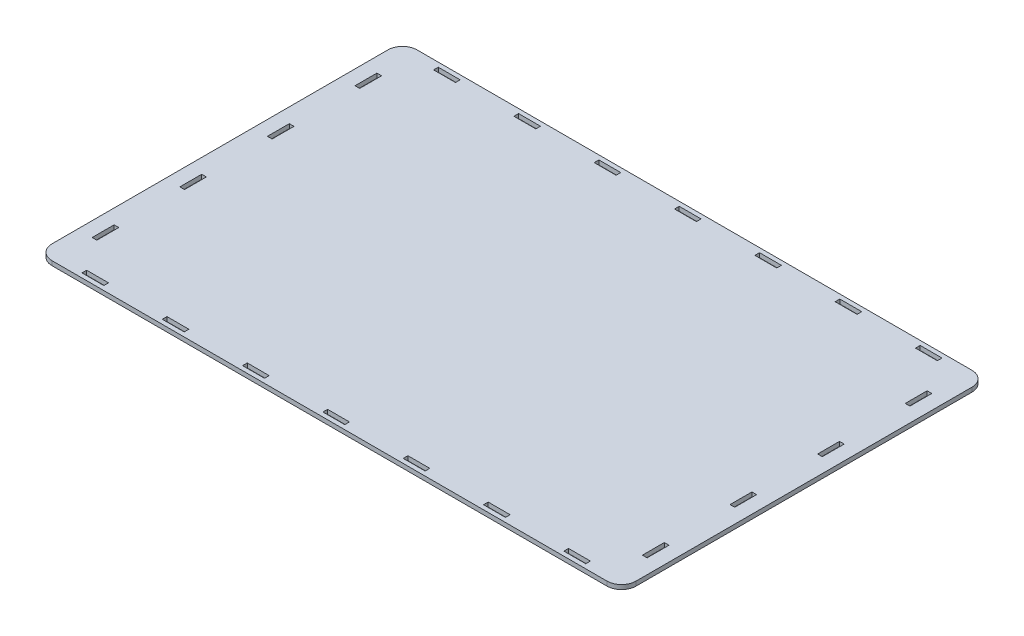
SolidWorks part; units mm, degrees
ref_plane "Front Plane" through (0, 0, 0) normal (0, 0, 1) x (1, 0, 0)
ref_plane "Top Plane" through (0, 0, 0) normal (0, 1, 0) x (1, 0, 0)
ref_plane "Right Plane" through (0, 0, 0) normal (1, 0, 0) x (0, 0, -1)
sketch "Sketch1" plane through (0, 0, 0) normal (0, 1, 0) x (1, 0, 0)
  line L0 (82.5, 3) -> (82.5, 6.2)
  line L1 (0, 0) -> (400, 0)
  line L2 (0, 0) -> (0, 250)
  line L3 (0, 250) -> (400, 250)
  line L5 (27.5, 3) -> (42.5, 3)
  line L6 (27.5, 3) -> (27.5, 6.2)
  line L7 (27.5, 6.2) -> (42.5, 6.2)
  line L8 (42.5, 3) -> (42.5, 6.2)
  line L9 (82.5, 3) -> (97.5, 3)
  line L10 (97.5, 3) -> (97.5, 6.2)
  line L11 (82.5, 6.2) -> (97.5, 6.2)
  line L12 (137.5, 3) -> (137.5, 6.2)
  line L13 (137.5, 3) -> (152.5, 3)
  line L14 (152.5, 3) -> (152.5, 6.2)
  line L15 (137.5, 6.2) -> (152.5, 6.2)
  line L16 (192.5, 3) -> (192.5, 6.2)
  line L17 (192.5, 3) -> (207.5, 3)
  line L18 (207.5, 3) -> (207.5, 6.2)
  line L19 (192.5, 6.2) -> (207.5, 6.2)
  line L20 (247.5, 3) -> (247.5, 6.2)
  line L21 (247.5, 3) -> (262.5, 3)
  line L22 (262.5, 3) -> (262.5, 6.2)
  line L23 (247.5, 6.2) -> (262.5, 6.2)
  line L24 (302.5, 3) -> (302.5, 6.2)
  line L25 (302.5, 3) -> (317.5, 3)
  line L26 (317.5, 3) -> (317.5, 6.2)
  line L27 (302.5, 6.2) -> (317.5, 6.2)
  line L28 (357.5, 3) -> (357.5, 6.2)
  line L29 (357.5, 3) -> (372.5, 3)
  line L30 (372.5, 3) -> (372.5, 6.2)
  line L31 (357.5, 6.2) -> (372.5, 6.2)
  line L32 (0, 125) -> (400, 125) construction
  line L33 (357.5, 247) -> (372.5, 247)
  line L34 (372.5, 247) -> (372.5, 243.8)
  line L35 (357.5, 243.8) -> (372.5, 243.8)
  line L36 (357.5, 247) -> (357.5, 243.8)
  line L37 (302.5, 247) -> (317.5, 247)
  line L38 (317.5, 247) -> (317.5, 243.8)
  line L39 (302.5, 243.8) -> (317.5, 243.8)
  line L40 (302.5, 247) -> (302.5, 243.8)
  line L41 (247.5, 247) -> (262.5, 247)
  line L42 (262.5, 247) -> (262.5, 243.8)
  line L43 (247.5, 243.8) -> (262.5, 243.8)
  line L44 (247.5, 247) -> (247.5, 243.8)
  line L45 (192.5, 247) -> (207.5, 247)
  line L46 (207.5, 247) -> (207.5, 243.8)
  line L47 (192.5, 243.8) -> (207.5, 243.8)
  line L48 (192.5, 247) -> (192.5, 243.8)
  line L49 (27.5, 243.8) -> (42.5, 243.8)
  line L50 (42.5, 247) -> (42.5, 243.8)
  line L51 (27.5, 247) -> (42.5, 247)
  line L52 (27.5, 247) -> (27.5, 243.8)
  line L53 (82.5, 247) -> (97.5, 247)
  line L54 (97.5, 247) -> (97.5, 243.8)
  line L55 (82.5, 243.8) -> (97.5, 243.8)
  line L56 (82.5, 247) -> (82.5, 243.8)
  line L57 (137.5, 247) -> (152.5, 247)
  line L58 (152.5, 247) -> (152.5, 243.8)
  line L59 (137.5, 243.8) -> (152.5, 243.8)
  line L60 (137.5, 247) -> (137.5, 243.8)
  line L61 (200, 0) -> (200, 250) construction
  line L62 (10, 102.5) -> (10, 87.5)
  line L63 (10, 42.5) -> (13.2, 42.5)
  line L64 (10, 42.5) -> (10, 27.5)
  line L65 (10, 27.5) -> (13.2, 27.5)
  line L66 (13.2, 42.5) -> (13.2, 27.5)
  line L67 (10, 102.5) -> (13.2, 102.5)
  line L68 (13.2, 102.5) -> (13.2, 87.5)
  line L69 (10, 87.5) -> (13.2, 87.5)
  line L70 (10, 162.5) -> (10, 147.5)
  line L71 (10, 162.5) -> (13.2, 162.5)
  line L72 (13.2, 162.5) -> (13.2, 147.5)
  line L73 (10, 147.5) -> (13.2, 147.5)
  line L74 (10, 222.5) -> (10, 207.5)
  line L75 (10, 222.5) -> (13.2, 222.5)
  line L76 (13.2, 222.5) -> (13.2, 207.5)
  line L77 (10, 207.5) -> (13.2, 207.5)
  line L78 (390, 27.5) -> (386.8, 27.5)
  line L79 (386.8, 42.5) -> (386.8, 27.5)
  line L80 (390, 42.5) -> (386.8, 42.5)
  line L81 (390, 42.5) -> (390, 27.5)
  line L82 (390, 102.5) -> (386.8, 102.5)
  line L83 (386.8, 102.5) -> (386.8, 87.5)
  line L84 (390, 87.5) -> (386.8, 87.5)
  line L85 (390, 102.5) -> (390, 87.5)
  line L86 (390, 162.5) -> (386.8, 162.5)
  line L87 (386.8, 162.5) -> (386.8, 147.5)
  line L88 (390, 147.5) -> (386.8, 147.5)
  line L89 (390, 162.5) -> (390, 147.5)
  line L90 (390, 222.5) -> (386.8, 222.5)
  line L91 (386.8, 222.5) -> (386.8, 207.5)
  line L92 (390, 207.5) -> (386.8, 207.5)
  line L93 (390, 222.5) -> (390, 207.5)
  line L99 (400, 0) -> (400, 250)
  dimension "D1" = 400
  dimension "D2" = 250
  dimension "D3" = 15
  dimension "D4" = 3.2
  dimension "D5" = 3
  dimension "D6" = 27.5
  dimension "D8" = 40
  dimension "D9" = 15
  dimension "D10" = 3.2
  dimension "D11" = 27.5
  dimension "D12" = 10
  dimension "D14" = 45
  dimension "D7" = 7
  dimension "D13" = 4
extrude "Boss-Extrude2" add sketch "Sketch1" along normal blind 3
fillet "Fillet1" radius 10 4 edges at (0, 1.5, -250) (0, 1.5, 0) (400, 1.5, -250) (400, 1.5, 0)
